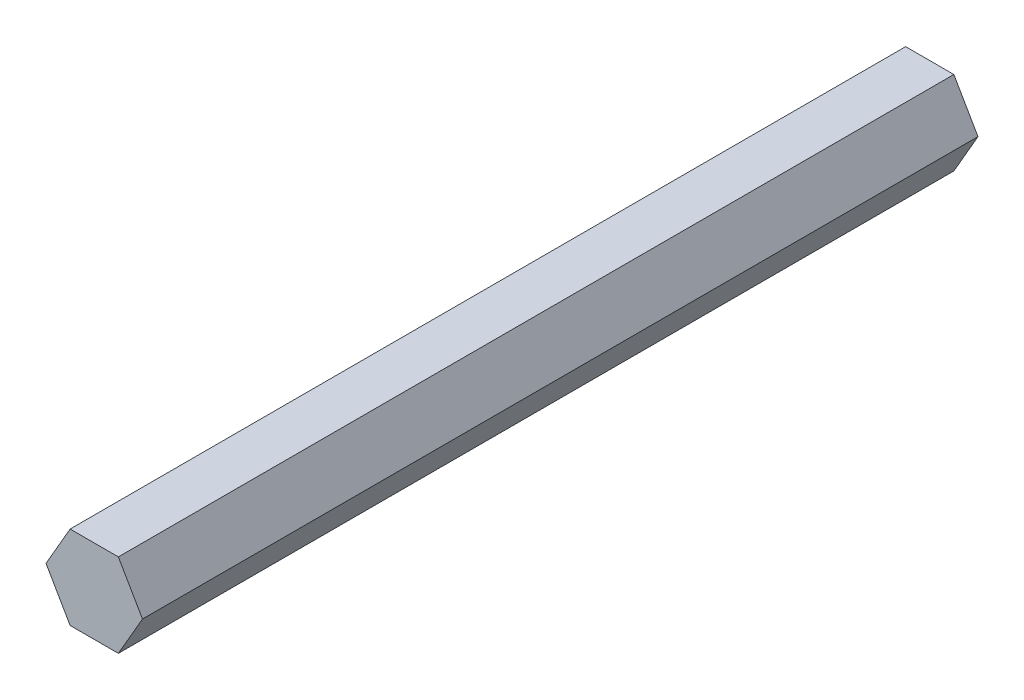
SolidWorks part; units mm, degrees
ref_plane "Front Plane" through (0, 0, 0) normal (0, 0, 1) x (1, 0, 0)
ref_plane "Top Plane" through (0, 0, 0) normal (0, 1, 0) x (1, 0, 0)
ref_plane "Right Plane" through (0, 0, 0) normal (1, 0, 0) x (0, 0, -1)
sketch "Sketch1" plane through (0, 0, 0) normal (0, 0, 1) x (1, 0, 0)
  line L1 (7.3323, 0) -> (3.6662, 6.35)
  line L2 (3.6662, 6.35) -> (-3.6662, 6.35)
  line L3 (-3.6662, 6.35) -> (-7.3323, 0)
  line L4 (-7.3323, 0) -> (-3.6662, -6.35)
  line L5 (-3.6662, -6.35) -> (3.6662, -6.35)
  line L6 (3.6662, -6.35) -> (7.3323, 0)
  circle A0 centre (0, 0) radius 6.35 construction
  dimension "D1" = 12.7
extrude "Boss-Extrude1" add sketch "Sketch1" along normal blind 127
